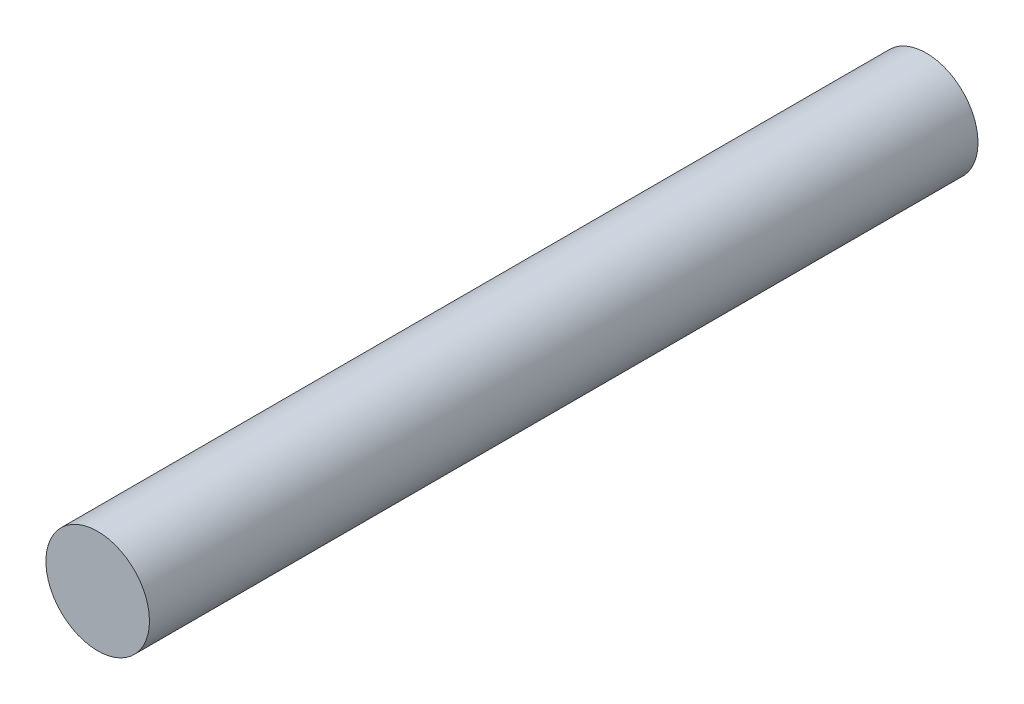
SolidWorks part; units mm, degrees
ref_plane "Front Plane" through (0, 0, 0) normal (0, 0, 1) x (1, 0, 0)
ref_plane "Top Plane" through (0, 0, 0) normal (0, 1, 0) x (1, 0, 0)
ref_plane "Right Plane" through (0, 0, 0) normal (1, 0, 0) x (0, 0, -1)
sketch "Sketch1" plane through (0, 0, 0) normal (0, 0, 1) x (1, 0, 0)
  circle A0 centre (0, 0) radius 1.5875
  dimension "D1" = 3.175
extrude "Boss-Extrude1" add sketch "Sketch1" along normal blind 25.4
equation "\"Din\"= 0.125in'diameter in "
equation "\"D1@Sketch1\"=\"Din\""
